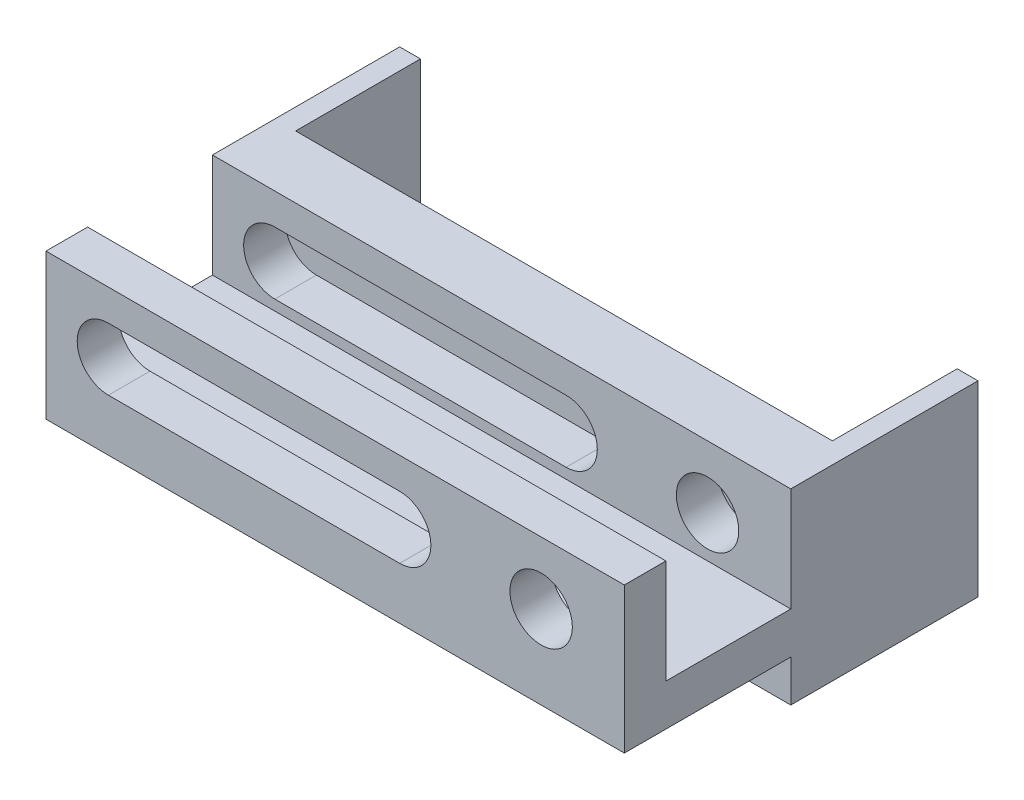
SolidWorks part; units mm, degrees
ref_plane "Front Plane" through (0, 0, 0) normal (0, 0, 1) x (1, 0, 0)
ref_plane "Top Plane" through (0, 0, 0) normal (0, 1, 0) x (1, 0, 0)
ref_plane "Right Plane" through (0, 0, 0) normal (1, 0, 0) x (0, 0, -1)
sketch "Sketch3" plane through (0, 0, 0) normal (1, 0, 0) x (0, 0, -1)
  line L0 (-27.8081, 35) -> (-27.8081, 10)
  line L2 (-37.8081, 0) -> (-37.8081, 35)
  line L3 (-37.8081, 35) -> (-27.8081, 35)
  line L4 (12.1919, 0) -> (12.1919, 35)
  line L5 (-27.8081, 10) -> (2.1919, 10)
  line L6 (2.1919, 10) -> (2.1919, 35)
  line L7 (2.1919, 35) -> (12.1919, 35)
  line L8 (-37.8081, 0) -> (2.1919, 0)
  line L17 (2.1919, 0) -> (2.1919, -10)
  line L18 (2.1919, -10) -> (47.1919, -10)
  line L19 (47.1919, -10) -> (47.1919, 0)
  line L20 (47.1919, 0) -> (12.1919, 0)
  dimension "D1" = 50
  dimension "D2" = 10
  dimension "D3" = 10
  dimension "D4" = 35
  dimension "D5" = 35
  dimension "D6" = 40
  dimension "D7" = 10
extrude "Boss-Extrude1" add sketch "Sketch3" along normal blind 139
sketch "Sketch5" plane through (0, 0, -12.1919) normal (0, 0, -1) x (-1, 0, 0)
  line L0 (-85, 20) -> (-15, 20) construction
  line L1 (-85, 27.5) -> (-15, 27.5)
  line L2 (-85, 12.5) -> (-15, 12.5)
  line L3 (-139, 0) -> (-139, 35) construction
  line L5 (0, 0) -> (0, 35) construction
  line L6 (-139, 35) -> (0, 35) construction
  circle A0 centre (-119, 20) radius 7.5
  arc A1 (-85, 27.5) -> (-85, 12.5) centre (-85, 20) ccw
  arc A2 (-15, 12.5) -> (-15, 27.5) centre (-15, 20) ccw
  point P2 (-50, 20)
  dimension "D1" = 15
  dimension "D2" = 15
  dimension "D3" = 20
  dimension "D4" = 15
  dimension "D5" = 15
  dimension "D6" = 70
extrude "Cut-Extrude1" cut sketch "Sketch5" against normal through all
sketch "Sketch6" plane through (0, 0, 0) normal (0, 1, 0) x (1, 0, 0)
  line L0 (139, 47.1919) -> (0, 47.1919) construction
  line L1 (0, 12.1919) -> (5, 12.1919)
  line L2 (0, 12.1919) -> (0, 47.1919)
  line L3 (0, 47.1919) -> (5, 47.1919)
  line L4 (5, 12.1919) -> (5, 47.1919)
  line L6 (139, 12.1919) -> (134, 12.1919)
  line L7 (139, 12.1919) -> (139, 47.1919)
  line L8 (139, 47.1919) -> (134, 47.1919)
  line L9 (134, 12.1919) -> (134, 47.1919)
  dimension "D1" = 5
extrude "Boss-Extrude2" add sketch "Sketch6" along normal up to surface (35 mm away) up to face at (69.5, 35, -7.1919)
sketch "Sketch7" plane through (0, 0, -12.1919) normal (0, 0, -1) x (-1, 0, 0)
  line L1 (-5, 0) -> (-134, 0)
  line L2 (-5, 0) -> (-5, 35)
  line L3 (-5, 35) -> (-134, 35)
  line L4 (-134, 0) -> (-134, 35)
extrude "Boss-Extrude3" add sketch "Sketch7" along normal blind 5
